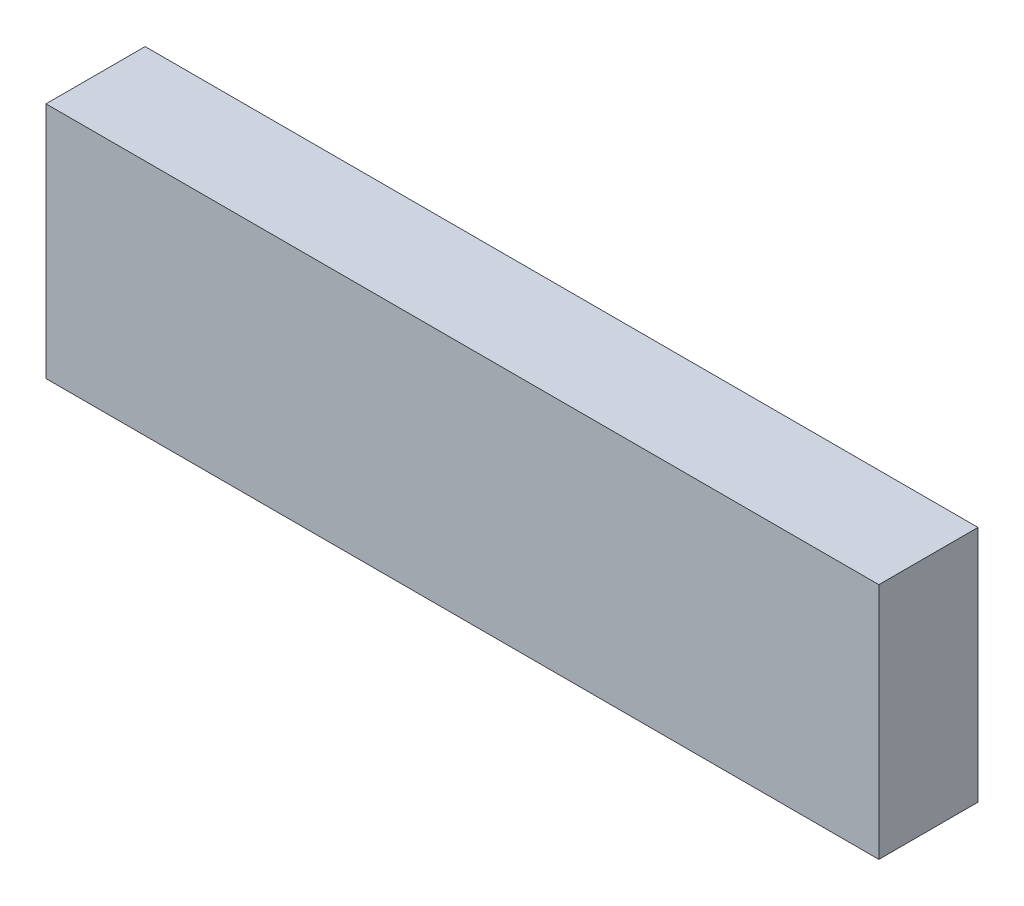
SolidWorks part; units mm, degrees
ref_plane "Front Plane" through (0, 0, 0) normal (0, 0, 1) x (1, 0, 0)
ref_plane "Top Plane" through (0, 0, 0) normal (0, 1, 0) x (1, 0, 0)
ref_plane "Right Plane" through (0, 0, 0) normal (1, 0, 0) x (0, 0, -1)
sketch "Sketch1" plane through (0, 0, 0) normal (0, 1, 0) x (1, 0, 0)
  line L1 (10.5, 1.25) -> (-10.5, 1.25)
  line L2 (10.5, 1.25) -> (10.5, -1.25)
  line L3 (10.5, -1.25) -> (-10.5, -1.25)
  line L4 (-10.5, 1.25) -> (-10.5, -1.25)
  line L5 (0, -1.25) -> (0, 1.25) construction
  line L6 (10.5, 0) -> (-10.5, 0) construction
  point P0 (0, 0)
  dimension "D1" = 21
  dimension "D2" = 2.5
extrude "Boss-Extrude1" add sketch "Sketch1" along normal mid plane 6
